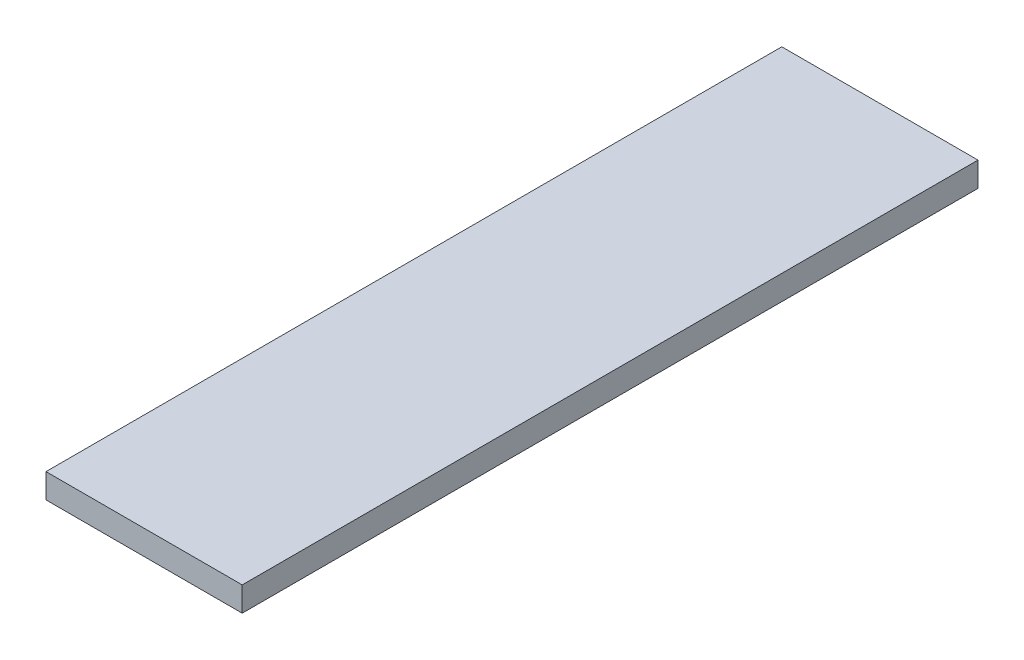
SolidWorks part; units mm, degrees
ref_plane "Front Plane" through (0, 0, 0) normal (0, 0, 1) x (1, 0, 0)
ref_plane "Top Plane" through (0, 0, 0) normal (0, 1, 0) x (1, 0, 0)
ref_plane "Right Plane" through (0, 0, 0) normal (1, 0, 0) x (0, 0, -1)
sketch "Sketch1" plane through (0, 0, 0) normal (0, 0, 1) x (1, 0, 0)
  line L7 (0, 0) -> (25.4, 0)
  line L8 (0, 0) -> (0, 6.35)
  line L9 (0, 6.35) -> (25.4, 6.35)
  line L10 (25.4, 0) -> (25.4, 6.35)
  dimension "D1" = 25.4
  dimension "D2" = 6.35
extrude "Boss-Extrude1" add sketch "Sketch1" along normal blind 190.5 contours L7 L10 L9 L8
sketch "Sketch2" plane through (0, 6.35, 0) normal (0, 1, 0) x (1, 0, 0)
  line L0 (0, -177.8) -> (0, -171.45)
  line L1 (0, -190.5) -> (6.35, -190.5)
  line L2 (0, -190.5) -> (0, -184.15)
  line L3 (0, -184.15) -> (6.35, -184.15)
  line L4 (6.35, -190.5) -> (6.35, -184.15)
  line L5 (0, -177.8) -> (6.35, -177.8)
  line L6 (6.35, -177.8) -> (6.35, -171.45)
  line L7 (0, -171.45) -> (6.35, -171.45)
  line L8 (0, -165.1) -> (0, -158.75)
  line L9 (0, -165.1) -> (6.35, -165.1)
  line L10 (6.35, -165.1) -> (6.35, -158.75)
  line L11 (0, -158.75) -> (6.35, -158.75)
  line L12 (0, -152.4) -> (0, -146.05)
  line L13 (0, -152.4) -> (6.35, -152.4)
  line L14 (6.35, -152.4) -> (6.35, -146.05)
  line L15 (0, -146.05) -> (6.35, -146.05)
  line L16 (0, -139.7) -> (0, -133.35)
  line L17 (0, -139.7) -> (6.35, -139.7)
  line L18 (6.35, -139.7) -> (6.35, -133.35)
  line L19 (0, -133.35) -> (6.35, -133.35)
  line L20 (0, -127) -> (0, -120.65)
  line L21 (0, -127) -> (6.35, -127)
  line L22 (6.35, -127) -> (6.35, -120.65)
  line L23 (0, -120.65) -> (6.35, -120.65)
  line L24 (0, -114.3) -> (0, -107.95)
  line L25 (0, -114.3) -> (6.35, -114.3)
  line L26 (6.35, -114.3) -> (6.35, -107.95)
  line L27 (0, -107.95) -> (6.35, -107.95)
  line L28 (0, -101.6) -> (0, -95.25)
  line L29 (0, -101.6) -> (6.35, -101.6)
  line L30 (6.35, -101.6) -> (6.35, -95.25)
  line L31 (0, -95.25) -> (6.35, -95.25)
  line L32 (0, -88.9) -> (0, -82.55)
  line L33 (0, -88.9) -> (6.35, -88.9)
  line L34 (6.35, -88.9) -> (6.35, -82.55)
  line L35 (0, -82.55) -> (6.35, -82.55)
  line L36 (0, -76.2) -> (0, -69.85)
  line L37 (0, -76.2) -> (6.35, -76.2)
  line L38 (6.35, -76.2) -> (6.35, -69.85)
  line L39 (0, -69.85) -> (6.35, -69.85)
  line L40 (0, -63.5) -> (0, -57.15)
  line L41 (0, -63.5) -> (6.35, -63.5)
  line L42 (6.35, -63.5) -> (6.35, -57.15)
  line L43 (0, -57.15) -> (6.35, -57.15)
  line L44 (0, -50.8) -> (0, -44.45)
  line L45 (0, -50.8) -> (6.35, -50.8)
  line L46 (6.35, -50.8) -> (6.35, -44.45)
  line L47 (0, -44.45) -> (6.35, -44.45)
  line L48 (0, -38.1) -> (0, -31.75)
  line L49 (0, -38.1) -> (6.35, -38.1)
  line L50 (6.35, -38.1) -> (6.35, -31.75)
  line L51 (0, -31.75) -> (6.35, -31.75)
  line L52 (0, -25.4) -> (0, -19.05)
  line L53 (0, -25.4) -> (6.35, -25.4)
  line L54 (6.35, -25.4) -> (6.35, -19.05)
  line L55 (0, -19.05) -> (6.35, -19.05)
  line L56 (0, -12.7) -> (0, -6.35)
  line L57 (0, -12.7) -> (6.35, -12.7)
  line L58 (6.35, -12.7) -> (6.35, -6.35)
  line L59 (0, -6.35) -> (6.35, -6.35)
  dimension "D1" = 6.35
  dimension "D2" = 6.35
  dimension "D3" = 15
extrude "Cut-Extrude1" [suppressed] cut sketch "Sketch2" against normal up to next
mirror "Mirror1" about plane through (25.4, 0, 190.5) normal (-1, 0, 0) of bodies 101 102
